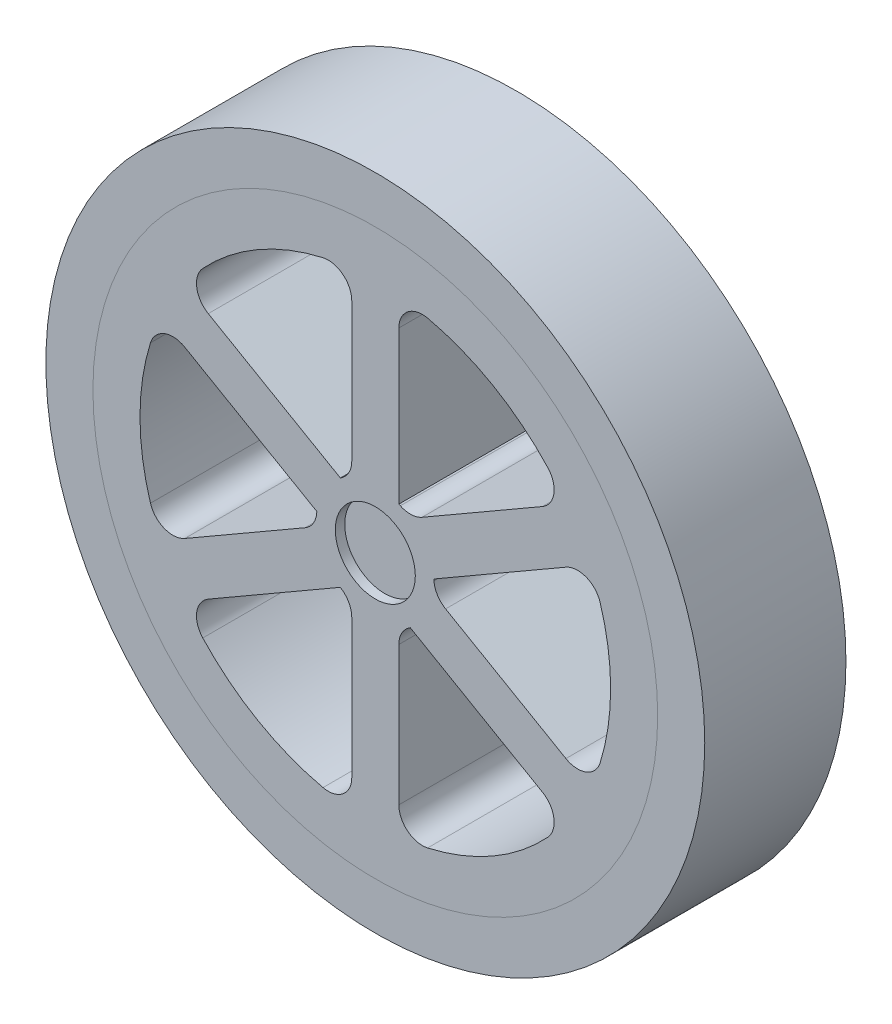
SolidWorks part; units mm, degrees
material "ABS"
ref_plane "正面" through (0, 0, 0) normal (0, 0, 1) x (1, 0, 0)
ref_plane "平面" through (0, 0, 0) normal (0, 1, 0) x (1, 0, 0)
ref_plane "右側面" through (0, 0, 0) normal (1, 0, 0) x (0, 0, -1)
sketch "ｽｹｯﾁ1" plane through (0, 0, 0) normal (0, 0, 1) x (1, 0, 0)
  line L0 (-5, 43.8748) -> (-5, 14.3614)
  line L1 (-5, -14.3614) -> (-5, -43.8748)
  line L2 (0, -12.5) -> (0, 12.5) construction
  line L3 (35.4967, 26.2675) -> (9.9373, 11.5108)
  line L4 (-14.9373, -2.8506) -> (-40.4967, -17.6073)
  line L5 (40.4967, -17.6073) -> (14.9373, -2.8506)
  line L6 (-7.4216, 10.0583) -> (-35.4967, 26.2675)
  line L7 (5, -43.8748) -> (5, -14.3614)
  line L8 (5, 11.4564) -> (5, 43.8748)
  line L9 (-35.4967, -26.2675) -> (-7.4216, -10.0583)
  line L10 (12.4216, 1.3981) -> (40.4967, 17.6073)
  line L11 (-40.4967, 17.6073) -> (-12.4216, 1.3981)
  line L12 (7.4216, -10.0583) -> (35.4967, -26.2675)
  circle A0 centre (0, 0) radius 60
  arc A1 (-12.4216, 1.3981) -> (-12.4552, 1.0568) centre (0, 0) ccw
  arc A2 (-47.7741, 14.7524) -> (-47.7741, -14.7524) centre (0, 0) ccw
  arc A3 (-7.4216, -10.0583) -> (-7.1429, -10.2581) centre (0, 0) ccw
  arc A4 (7.1429, -10.2581) -> (7.4216, -10.0583) centre (0, 0) ccw
  arc A5 (12.4552, 1.0568) -> (12.4216, 1.3981) centre (0, 0) ccw
  arc A6 (5.3124, 11.315) -> (5, 11.4564) centre (0, 0) ccw
  arc A7 (-7.1429, 10.2581) -> (-7.4216, 10.0583) centre (0, 0) ccw
  arc A8 (-36.663, -33.9974) -> (-11.1111, -48.7498) centre (0, 0) ccw
  arc A9 (11.1111, -48.7498) -> (36.663, -33.9974) centre (0, 0) ccw
  arc A10 (47.7741, -14.7524) -> (47.7741, 14.7524) centre (0, 0) ccw
  arc A11 (36.663, 33.9974) -> (11.1111, 48.7498) centre (0, 0) ccw
  arc A12 (-11.1111, 48.7498) -> (-36.663, 33.9974) centre (0, 0) ccw
  arc A13 (35.4967, -26.2675) -> (36.663, -33.9974) centre (32.9967, -30.5977) cw
  arc A14 (-40.4967, 17.6073) -> (-47.7741, 14.7524) centre (-42.9967, 13.2772) ccw
  arc A15 (40.4967, 17.6073) -> (47.7741, 14.7524) centre (42.9967, 13.2772) cw
  arc A16 (-35.4967, -26.2675) -> (-36.663, -33.9974) centre (-32.9967, -30.5977) ccw
  arc A17 (5, 43.8748) -> (11.1111, 48.7498) centre (10, 43.8748) cw
  arc A18 (5, -14.3614) -> (7.1429, -10.2581) centre (10, -14.3614) cw
  arc A19 (5, -43.8748) -> (11.1111, -48.7498) centre (10, -43.8748) ccw
  arc A20 (-35.4967, 26.2675) -> (-36.663, 33.9974) centre (-32.9967, 30.5977) cw
  arc A21 (14.9373, -2.8506) -> (12.4552, 1.0568) centre (17.4373, 1.4796) cw
  arc A22 (40.4967, -17.6073) -> (47.7741, -14.7524) centre (42.9967, -13.2772) ccw
  arc A23 (-40.4967, -17.6073) -> (-47.7741, -14.7524) centre (-42.9967, -13.2772) cw
  arc A24 (-14.9373, -2.8506) -> (-12.4552, 1.0568) centre (-17.4373, 1.4796) ccw
  arc A25 (9.9373, 11.5108) -> (5.3124, 11.315) centre (7.4373, 15.841) cw
  arc A26 (35.4967, 26.2675) -> (36.663, 33.9974) centre (32.9967, 30.5977) ccw
  arc A27 (-5, -43.8748) -> (-11.1111, -48.7498) centre (-10, -43.8748) cw
  arc A28 (-5, -14.3614) -> (-7.1429, -10.2581) centre (-10, -14.3614) ccw
  arc A29 (-5, 14.3614) -> (-7.1429, 10.2581) centre (-10, 14.3614) cw
  arc A30 (-5, 43.8748) -> (-11.1111, 48.7498) centre (-10, 43.8748) ccw
  point P12 (-17.5169, 12.8839)
  point P13 (0, 0)
  point P33 (0, 0)
  point P62 (-5, -49.7494)
  point P65 (-5, -11.4564)
  point P68 (-5, 11.4564)
  point P71 (-5, 49.7494)
  dimension "D1" = 120
  dimension "D2" = 25
  dimension "D3" = 100
  dimension "D6" = 5
  dimension "D4" = 10
  dimension "D5" = 6
extrude "ﾎﾞｽ - 押し出し1" add sketch "ｽｹｯﾁ1" along normal blind 30
sketch "ｽｹｯﾁ2" plane through (0, 0, 30) normal (0, 0, 1) x (1, 0, 0)
  circle A0 centre (0, 0) radius 70
  circle A1 centre (0, 0) radius 60 construction
  circle A2 centre (0, 0) radius 60
  dimension "D1" = 10
extrude "ﾎﾞｽ - 押し出し2" add sketch "ｽｹｯﾁ2" against normal up to surface (30 mm away) separate body up to face at (31.354, -0.1, 0)
sketch "ｽｹｯﾁ3" plane through (0, 0, 30) normal (0, 0, 1) x (1, 0, 0)
  circle A0 centre (0, 0) radius 8.5
  dimension "D1" = 17
extrude "ｶｯﾄ - 押し出し1" cut sketch "ｽｹｯﾁ3" against normal blind 2
